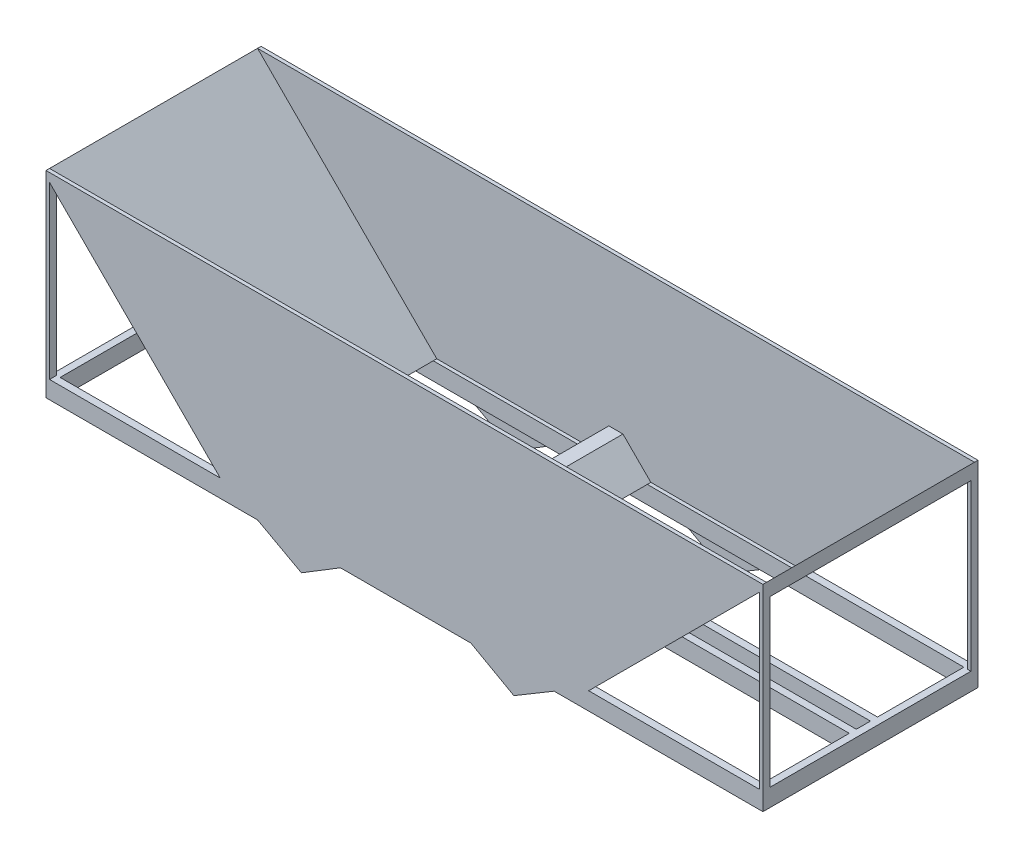
SolidWorks part; units mm, degrees
material "Custom Plastic"
ref_plane "Front Plane" through (0, 0, 0) normal (0, 0, 1) x (1, 0, 0)
ref_plane "Top Plane" through (0, 0, 0) normal (0, 1, 0) x (1, 0, 0)
ref_plane "Right Plane" through (0, 0, 0) normal (1, 0, 0) x (0, 0, -1)
sketch "Sketch1" plane through (0, 0, 0) normal (0, 1, 0) x (1, 0, 0)
  line L1 (-508, 152.4) -> (508, 152.4)
  line L2 (-508, 152.4) -> (-508, -152.4)
  line L3 (-508, -152.4) -> (508, -152.4)
  line L4 (508, 152.4) -> (508, -152.4)
  line L5 (-498, 142.4) -> (498, 142.4)
  line L6 (-498, 142.4) -> (-498, -142.4)
  line L7 (-498, -142.4) -> (498, -142.4)
  line L8 (498, 142.4) -> (498, -142.4)
  point P9 (508, 0)
  dimension "D1" = 1016
  dimension "D2" = 304.8
  dimension "D3" = 152.4
  dimension "D4" = 508
  dimension "D5" = 10
  dimension "D6" = 10
  dimension "D7" = 10
  dimension "D8" = 10
extrude "Boss-Extrude1" add sketch "Sketch1" along normal blind 10 and the other way blind 15
sketch "Sketch2" plane through (0, 0, 0) normal (0, 1, 0) x (1, 0, 0)
  line L0 (-498, 142.4) -> (-498, -142.4) construction
  line L1 (-498, 20) -> (-30, 20)
  line L2 (-498, 20) -> (-498, 10)
  line L3 (-498, 10) -> (-10, 10)
  line L4 (498, 20) -> (498, 10)
  line L5 (498, -142.4) -> (498, 142.4) construction
  line L6 (498, 142.4) -> (-498, 142.4) construction
  line L7 (-498, -10) -> (-10, -10)
  line L8 (-498, -10) -> (-498, -20)
  line L9 (30, -20) -> (498, -20)
  line L10 (498, -10) -> (498, -20)
  line L11 (-20, 142.4) -> (-10, 142.4)
  line L12 (-20, 142.4) -> (-20, 30)
  line L13 (-20, -142.4) -> (-10, -142.4)
  line L14 (-10, 142.4) -> (-10, 20)
  line L15 (-498, -142.4) -> (498, -142.4) construction
  line L16 (-20, -30) -> (-20, -142.4)
  line L17 (10, 142.4) -> (20, 142.4)
  line L18 (10, 142.4) -> (10, 20)
  line L19 (10, -142.4) -> (20, -142.4)
  line L20 (20, 142.4) -> (20, 30)
  line L21 (-10, -20) -> (-10, -142.4)
  line L22 (10, -20) -> (10, -142.4)
  line L23 (20, -30) -> (20, -142.4)
  line L24 (-498, -20) -> (-30, -20)
  line L27 (10, -10) -> (498, -10)
  line L28 (10, 10) -> (498, 10)
  line L29 (-10, -10) -> (-10, -20)
  line L30 (10, -10) -> (10, -20)
  line L31 (-10, 20) -> (-10, 10)
  line L32 (10, 20) -> (10, 10)
  line L34 (30, 20) -> (498, 20)
  arc A0 (20, -30) -> (30, -20) centre (30, -30) cw
  arc A1 (-20, -30) -> (-30, -20) centre (-30, -30) ccw
  arc A2 (20, 30) -> (30, 20) centre (30, 30) ccw
  arc A3 (-20, 30) -> (-30, 20) centre (-30, 30) cw
  point P37 (-20, -20)
  point P44 (20, 20)
  dimension "D2" = 10
  dimension "D9" = 10
  dimension "D10" = 10
  dimension "D1" = 10
  dimension "D3" = 20
  dimension "D4" = 10
  dimension "D5" = 10
  dimension "D6" = 10
  dimension "D7" = 20
  dimension "D8" = 10
extrude "Boss-Extrude2" add sketch "Sketch2" along normal blind 10 and the other way blind 15
sketch "Sketch3" plane through (0, 0, 0) normal (0, 0, 1) x (1, 0, 0)
  line L0 (-508, 10) -> (-508, 264)
  line L1 (-508, 264) -> (-254, 10)
  line L2 (-508, 10) -> (508, 10) construction
  line L3 (-508, 10) -> (-503, 10)
  line L4 (0, 289.7) -> (0, -86.1151) construction
  line L8 (-503, 251.9289) -> (-503, 10)
  line L9 (-503, 251.9289) -> (-261.0711, 10)
  line L10 (-261.0711, 10) -> (-254, 10)
  line L11 (261.0711, 10) -> (254, 10)
  line L12 (503, 251.9289) -> (261.0711, 10)
  line L13 (503, 251.9289) -> (503, 10)
  line L14 (508, 10) -> (503, 10)
  line L15 (508, 264) -> (254, 10)
  line L16 (508, 10) -> (508, 264)
  dimension "D1" = 45
  dimension "D2" = 254
  dimension "D3" = 5
  dimension "D4" = 5
extrude "Boss-Extrude3" add sketch "Sketch3" along normal blind 152.4 and the other way blind 152.4
sketch "Sketch4" plane through (0, 10, 0) normal (0, 1, 0) x (1, 0, 0)
  line L0 (-30, 20) -> (-254, 20) construction
  line L1 (-253.9496, 20) -> (253.0996, 20)
  line L2 (-253.9496, 20) -> (-253.9496, -20)
  line L3 (-253.9496, -20) -> (253.0996, -20)
  line L4 (253.0996, 20) -> (253.0996, -20)
  line L5 (30, -20) -> (254, -20) construction
extrude "Boss-Extrude7" add sketch "Sketch4" along normal blind 5
sketch "Sketch5" plane through (508, 0, 0) normal (1, 0, 0) x (0, 0, -1)
  line L0 (-152.4, -15) -> (-152.4, 264) construction
  line L1 (-142.4, 244) -> (142.4, 244)
  line L2 (-142.4, 244) -> (-142.4, 10)
  line L3 (-142.4, 10) -> (142.4, 10)
  line L4 (142.4, 244) -> (142.4, 10)
  line L5 (152.4, -15) -> (152.4, 264) construction
  line L6 (152.4, 264) -> (-152.4, 264) construction
  line L7 (-152.4, -15) -> (152.4, -15) construction
  dimension "D1" = 10
  dimension "D2" = 10
  dimension "D3" = 20
  dimension "D4" = 25
extrude "Cut-Extrude1" cut sketch "Sketch5" against normal blind 15
sketch "Sketch6" plane through (-508, 0, 0) normal (-1, 0, 0) x (0, 0, 1)
  line L0 (-152.4, 264) -> (152.4, 264) construction
  line L1 (-142.4, 244) -> (142.4, 244)
  line L2 (-142.4, 244) -> (-142.4, 10)
  line L3 (-142.4, 10) -> (142.4, 10)
  line L4 (142.4, 244) -> (142.4, 10)
  line L5 (-152.4, -15) -> (-152.4, 264) construction
  line L6 (152.4, -15) -> (152.4, 264) construction
  line L7 (-152.4, -15) -> (152.4, -15) construction
  dimension "D1" = 20
  dimension "D2" = 10
  dimension "D3" = 10
  dimension "D4" = 25
extrude "Cut-Extrude2" cut sketch "Sketch6" against normal blind 15
sketch "Sketch7" plane through (0, 0, -152.4) normal (0, 0, -1) x (-1, 0, 0)
  line L0 (-49.3858, 10) -> (-9.8479, 49.5379)
  line L1 (-9.8479, 49.5379) -> (10.1521, 49.5379)
  line L2 (10.1521, 49.5379) -> (49.69, 10)
  line L3 (-49.3858, 10) -> (49.69, 10)
  line L6 (-254, 10) -> (254, 10) construction
  point P2 (0, 0)
  point P5 (0, 0)
  point P9 (0, 0)
  point P10 (0, 0)
  dimension "D1" = 45
  dimension "D2" = 45
  dimension "D3" = 20
  dimension "D4" = 49.69
extrude "Boss-Extrude8" add sketch "Sketch7" against normal blind 304.8
sketch "Sketch8" plane through (0, 0, 152.4) normal (0, 0, 1) x (1, 0, 0)
  line L0 (-508, 264) -> (508, 264)
  line L1 (508, 264) -> (254, 10)
  line L2 (254, 10) -> (-254, 10)
  line L3 (-254, 10) -> (-508, 264)
extrude "Boss-Extrude9" add sketch "Sketch8" against normal blind 5
sketch "Sketch9" plane through (0, 0, -152.4) normal (0, 0, -1) x (-1, 0, 0)
  line L0 (-508, 264) -> (508, 264)
  line L1 (508, 264) -> (254, 10)
  line L2 (254, 10) -> (-254, 10)
  line L3 (-254, 10) -> (-508, 264)
extrude "Boss-Extrude10" add sketch "Sketch9" against normal blind 5
sketch "Sketch10" plane through (0, 0, 152.4) normal (0, 0, 1) x (1, 0, 0)
  line L0 (-254, 10) -> (-146.085, -48.8385)
  line L1 (-146.085, -48.8385) -> (-49.69, 10)
  line L2 (-254, 10) -> (-261.0711, 10) construction
  line L3 (-49.69, 10) -> (-10.1521, 49.5379) construction
  line L4 (-10, 10) -> (-253.9496, 10) construction
  line L5 (49.3858, 10) -> (155.0711, -49.0187)
  line L6 (155.0711, -49.0187) -> (254, 10)
  line L7 (-254, 10) -> (-49.69, 10)
  line L8 (49.3858, 10) -> (254, 10)
  dimension "D1" = 120
  dimension "D2" = 120
extrude "Boss-Extrude11" add sketch "Sketch10" against normal blind 5
sketch "Sketch11" plane through (0, 0, -152.4) normal (0, 0, -1) x (-1, 0, 0)
  line L0 (-212.0943, -15) -> (-155.0711, -49.0187)
  line L1 (-155.0711, -49.0187) -> (-94.1535, -15)
  line L2 (-94.1535, -15) -> (-212.0943, -15)
  line L3 (90.6474, -15) -> (146.085, -48.8385)
  line L4 (146.085, -48.8385) -> (208.1478, -15)
  line L5 (208.1478, -15) -> (90.6474, -15)
extrude "Boss-Extrude12" add sketch "Sketch11" against normal blind 5
